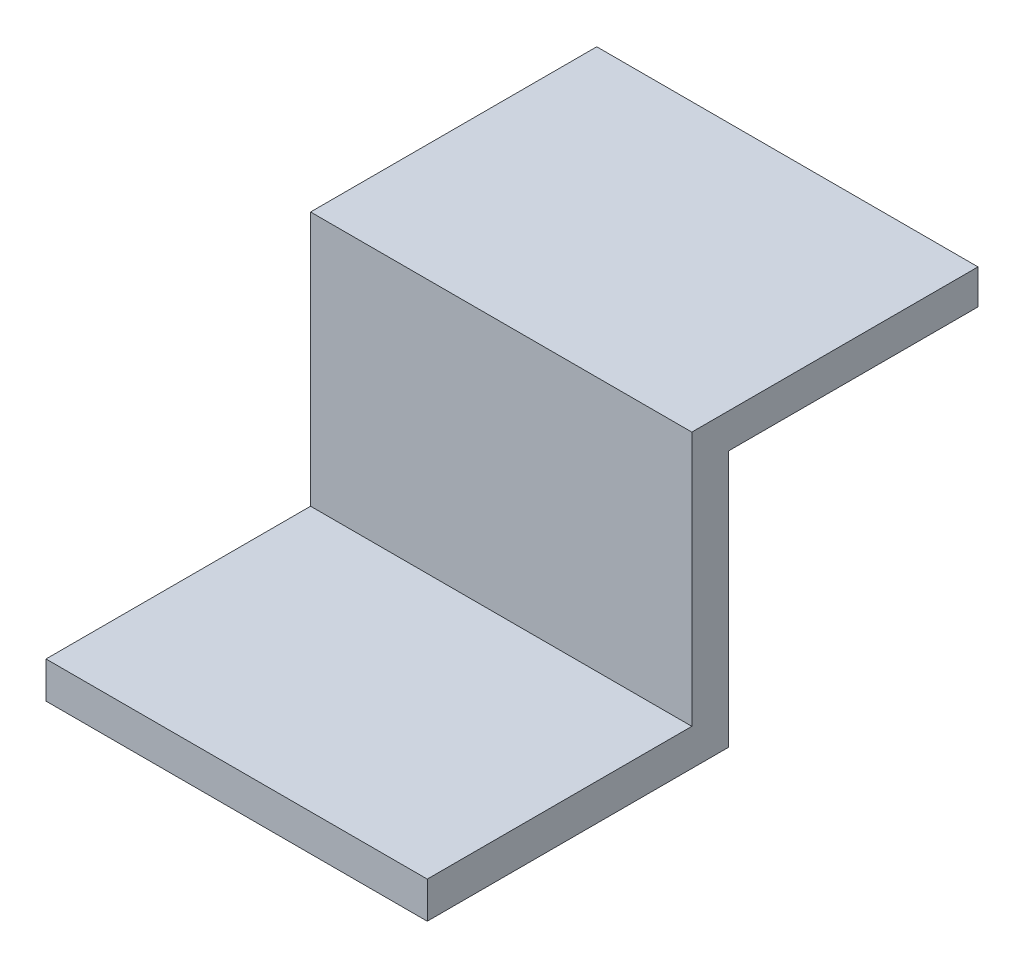
SolidWorks part; units mm, degrees
ref_plane "Front Plane" through (0, 0, 0) normal (0, 0, 1) x (1, 0, 0)
ref_plane "Top Plane" through (0, 0, 0) normal (0, 1, 0) x (1, 0, 0)
ref_plane "Right Plane" through (0, 0, 0) normal (1, 0, 0) x (0, 0, -1)
sketch "Sketch10" plane through (0, 0, 0) normal (1, 0, 0) x (0, 0, -1)
  line L0 (52.3533, 44.6272) -> (52.3533, 0)
  line L1 (52.3533, 0) -> (0, 0)
  line L2 (0, 0) -> (0, 6.35)
  line L3 (0, 6.35) -> (46.0033, 6.35)
  line L4 (46.0033, 6.35) -> (46.0033, 50.6588)
  line L5 (46.0033, 50.6588) -> (52.3533, 50.6588)
  line L7 (52.3533, 50.6588) -> (95.7628, 50.6588)
  line L9 (52.3533, 44.6272) -> (95.7628, 44.6272)
  line L10 (95.7628, 50.6588) -> (95.7628, 44.6272)
extrude "Extrude4" add sketch "Sketch10" against normal blind 66.294
ref_plane "Plane3" through (0, 3.2941, 3.1728) normal (0, -0.7202, -0.6937) x (1, 0, 0)
sketch "Sketch11" plane through (0, 3.2941, 3.1728) normal (0, -0.7202, -0.6937) x (1, 0, 0)
  line L0 (-33.147, -68.2766) -> (-33.147, -4.4051)
  line L5 (-66.294, -68.2766) -> (0, -68.2766) construction
  line L6 (-66.294, -4.4051) -> (0, -4.4051) construction
